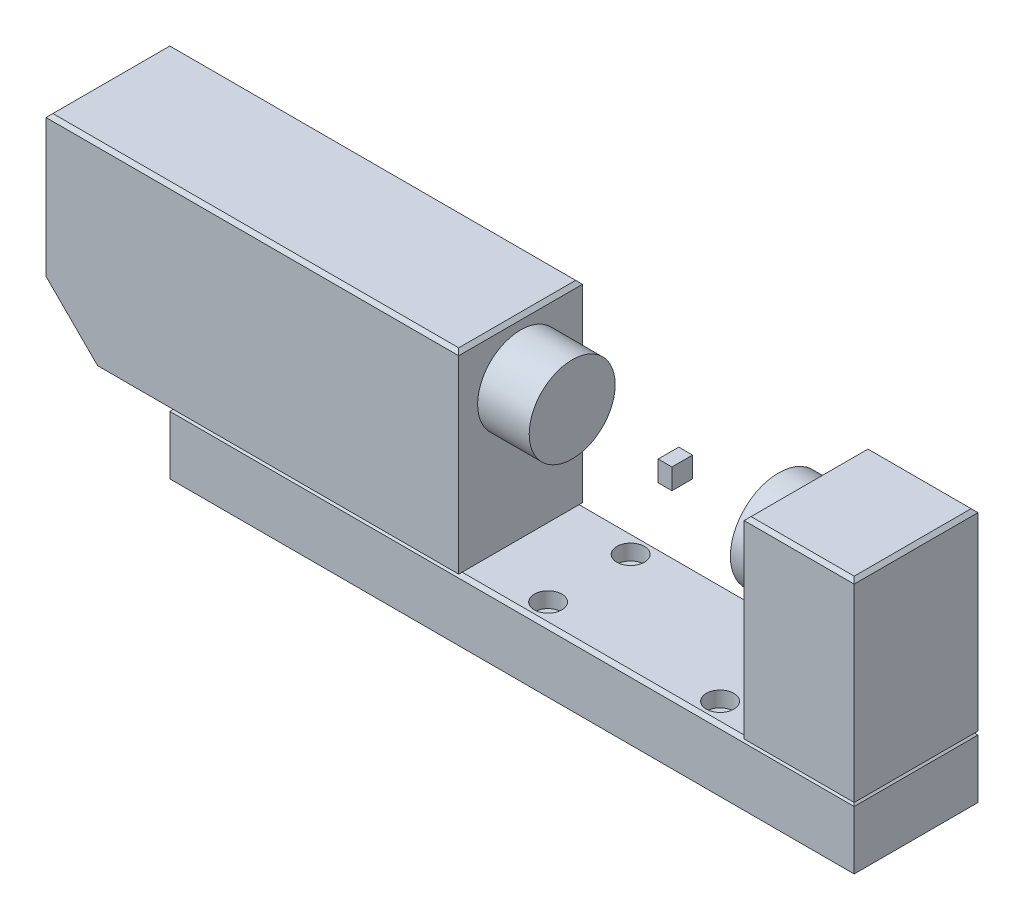
SolidWorks part; units mm, degrees
ref_plane "Front Plane" through (0, 0, 0) normal (0, 0, 1) x (1, 0, 0)
ref_plane "Top Plane" through (0, 0, 0) normal (0, 1, 0) x (1, 0, 0)
ref_plane "Right Plane" through (0, 0, 0) normal (1, 0, 0) x (0, 0, -1)
sketch "Sketch1" plane through (0, 0, 0) normal (0, 1, 0) x (1, 0, 0)
  line L0 (70, 0) -> (-129, 0) construction
  line L1 (-129, -18) -> (70, -18)
  line L2 (-129, -18) -> (-129, 18)
  line L3 (-129, 18) -> (70, 18)
  line L4 (70, -18) -> (70, 18)
  dimension "D1" = 199
  dimension "D2" = 70
  dimension "D3" = 36
extrude "Boss-Extrude1" add sketch "Sketch1" along normal blind 18
sketch "Sketch2" plane through (0, 18, 0) normal (0, 1, 0) x (1, 0, 0)
  line L0 (0, 18) -> (0, -18) construction
  line L1 (70, 18) -> (-129, 18) construction
  line L2 (-129, -18) -> (70, -18) construction
  line L3 (70, 0) -> (-129, 0) construction
  line L4 (70, -18) -> (70, 18) construction
  line L5 (-129, 18) -> (-129, -18) construction
  circle A0 centre (-25, 12) radius 4
  circle A1 centre (25, 12) radius 4
  circle A2 centre (25, -12) radius 4
  circle A3 centre (-25, -12) radius 4
  point P17 (-20.3745, 0)
  dimension "D1" = 8
  dimension "D2" = 25
  dimension "D3" = 12
extrude "Cut-Extrude1" cut sketch "Sketch2" against normal blind 4.5
sketch "Sketch3" plane through (0, 13.5, 0) normal (0, 1, 0) x (1, 0, 0)
  circle A0 centre (-25, 12) radius 2.25
  circle A1 centre (-25, -12) radius 2.25
  circle A2 centre (25, 12) radius 2.25
  circle A3 centre (25, -12) radius 2.25
  circle A4 centre (-25, -12) radius 4 construction
  dimension "D1" = 4.5
extrude "Cut-Extrude2" cut sketch "Sketch3" against normal up to next
chamfer "Chamfer1" distance 1 angle 45 4 edges at (70, 18, 0) (-29.5, 18, -18) (-129, 18, 0) (-29.5, 18, 18)
sketch "Sketch4" plane through (0, 18, 0) normal (0, 1, 0) x (1, 0, 0)
  line L0 (70, -18) -> (-129, -18) construction
  line L1 (-45, 18) -> (-165, 18)
  line L2 (-45, 18) -> (-45, -18)
  line L3 (-45, -18) -> (-165, -18)
  line L4 (-165, 18) -> (-165, -18)
  line L5 (38, 18) -> (70, 18)
  line L6 (38, 18) -> (38, -18)
  line L7 (38, -18) -> (70, -18)
  line L8 (70, 18) -> (70, -18)
  line L9 (-129, 18) -> (70, 18) construction
  line L10 (70, 18) -> (70, -18) construction
  dimension "D1" = 235
  dimension "D2" = 32
  dimension "D3" = 120
extrude "Boss-Extrude2" add sketch "Sketch4" along normal blind 56
chamfer "Chamfer2" distance 1 angle 45 8 edges at (54, 74, -18) (70, 74, 0) (54, 74, 18) (38, 74, 0) (-165, 74, 0) (-105, 74, -18) (-45, 74, 0) (-105, 74, 18)
chamfer "Chamfer3" distance 15 angle 45 1 edges at (-165, 18, 0)
sketch "Sketch5" plane through (-45, 0, 0) normal (1, 0, 0) x (0, 0, -1)
  line L0 (-17, 18) -> (17, 18) construction
  line L1 (0, 58) -> (0, 18) construction
  circle A0 centre (0, 58) radius 12.5
  dimension "D2" = 25
  dimension "D1" = 40
extrude "Boss-Extrude3" add sketch "Sketch5" along normal blind 15
sketch "Sketch6" plane through (38, 0, 0) normal (-1, 0, 0) x (0, 0, 1)
  line L0 (0, 58) -> (0, 18) construction
  line L1 (-17, 18) -> (17, 18) construction
  circle A0 centre (0, 58) radius 14
  dimension "D2" = 28
  dimension "D1" = 40
extrude "Boss-Extrude4" add sketch "Sketch6" along normal blind 8
ref_plane "Plane1" through (0, 0, 0) normal (1, 0, 0) x (0, 0, -1)
sketch "Sketch7" plane through (0, 0, 0) normal (1, 0, 0) x (0, 0, -1)
  line L0 (0, 61) -> (0, 0) construction
  line L1 (-3, 61) -> (3, 61)
  line L2 (-3, 61) -> (-3, 55)
  line L3 (-3, 55) -> (3, 55)
  line L4 (3, 61) -> (3, 55)
  line L5 (-3, 58) -> (3, 58) construction
  dimension "D1" = 58
  dimension "D2" = 6
  dimension "D3" = 6
extrude "Boss-Extrude5" add sketch "Sketch7" along normal mid plane 4 separate body
